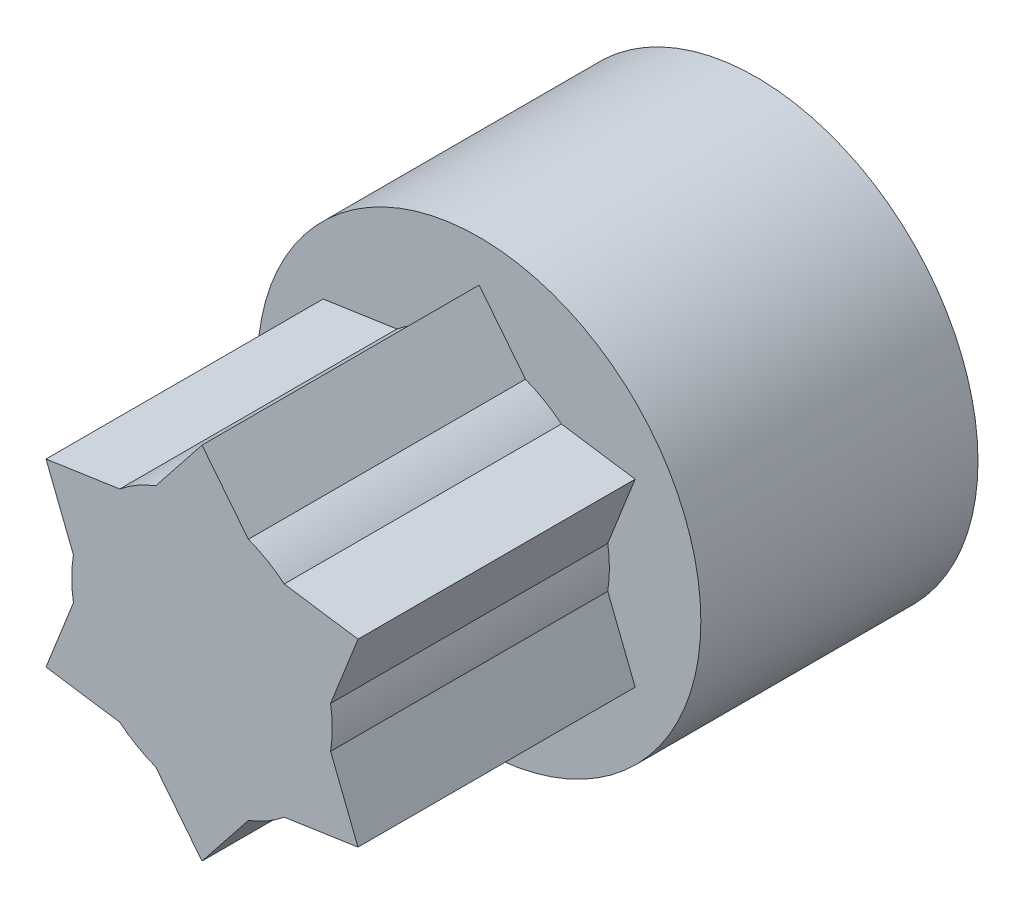
SolidWorks part; units mm, degrees
ref_plane "Спереди" through (0, 0, 0) normal (0, 0, 1) x (1, 0, 0)
ref_plane "Сверху" through (0, 0, 0) normal (0, 1, 0) x (1, 0, 0)
ref_plane "Справа" through (0, 0, 0) normal (1, 0, 0) x (0, 0, -1)
ref_plane "Плоскость1" through (0, 0, 31.603) normal (0, 0, 1) x (1, 0, 0)
sketch "Эскиз2" plane through (0, 0, 31.603) normal (0, 0, 1) x (1, 0, 0)
  line L2 (-0.836, 2.1963) -> (0, 3.25)
  line L3 (2.32, 0.3742) -> (2.8146, 1.625)
  line L4 (0.836, 2.1963) -> (0, 3.25)
  line L7 (1.484, 1.8221) -> (2.8146, 1.625)
  line L8 (1.484, -1.8221) -> (2.8146, -1.625)
  line L9 (2.32, -0.3742) -> (2.8146, -1.625)
  line L10 (-0.836, -2.1963) -> (0, -3.25)
  line L11 (0.836, -2.1963) -> (0, -3.25)
  line L12 (-2.32, -0.3742) -> (-2.8146, -1.625)
  line L13 (-1.484, -1.8221) -> (-2.8146, -1.625)
  line L14 (-1.484, 1.8221) -> (-2.8146, 1.625)
  line L15 (-2.32, 0.3742) -> (-2.8146, 1.625)
  circle A0 centre (0, 0) radius 4
  circle A1 centre (0, 0) radius 2.35
  point P24 (0, 0)
  point P25 (0, 0)
extrude "Бобышка-Вытянуть2" add sketch "Эскиз2" along normal blind 5 contours A1 | A1 L4 L2 | A1 L3 L7 | A1 L8 L9 | A1 L10 L11 | A1 L12 L13 | A1 L14 L15
sketch "Эскиз3" plane through (0, 0, 31.603) normal (0, 0, 1) x (1, 0, 0)
  circle A0 centre (0, 0) radius 4
extrude "Бобышка-Вытянуть4" add sketch "Эскиз3" against normal blind 5
